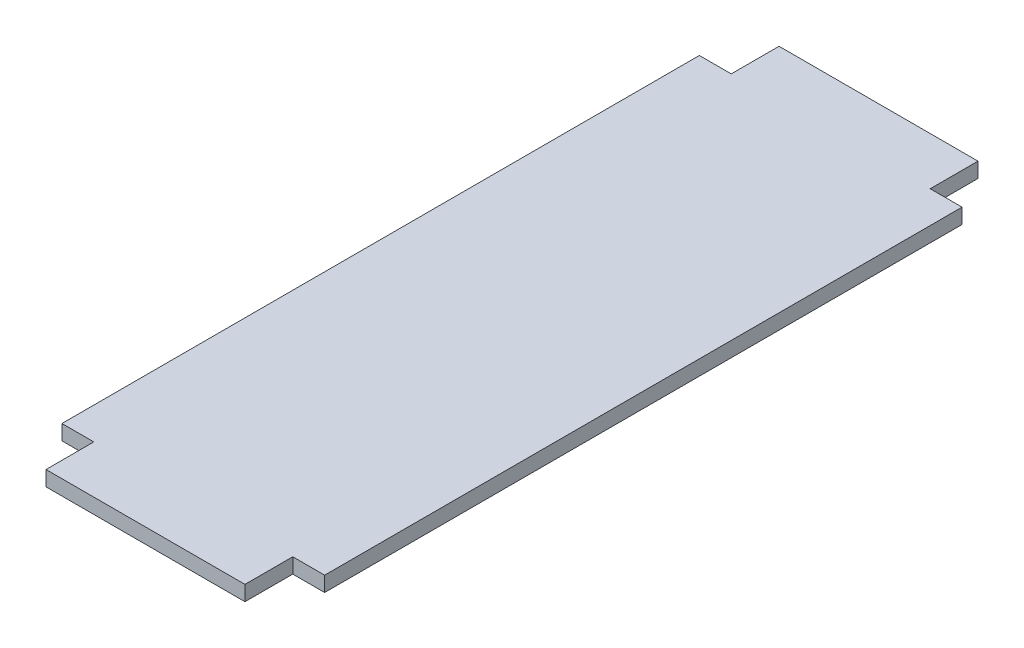
SolidWorks part; units mm, degrees
ref_plane "Front Plane" through (0, 0, 0) normal (0, 0, 1) x (1, 0, 0)
ref_plane "Top Plane" through (0, 0, 0) normal (0, 1, 0) x (1, 0, 0)
ref_plane "Right Plane" through (0, 0, 0) normal (1, 0, 0) x (0, 0, -1)
sketch "Sketch1" plane through (0, 0, 0) normal (0, 1, 0) x (1, 0, 0)
  line L0 (-26.169, 66.4972) -> (26.169, 66.4972) construction
  line L1 (26.169, -73.025) -> (-26.169, -73.025)
  line L2 (26.169, -73.025) -> (26.169, 73.025)
  line L3 (26.169, 73.025) -> (-26.169, 73.025)
  line L4 (-26.169, -73.025) -> (-26.169, 73.025)
  line L5 (26.169, -73.025) -> (-26.169, 73.025) construction
  line L6 (26.169, 73.025) -> (-26.169, -73.025) construction
  line L7 (-26.169, -66.4972) -> (26.169, -66.4972) construction
  line L8 (-26.169, 66.4972) -> (-26.169, -66.4972) construction
  line L9 (26.169, 66.4972) -> (26.169, -66.4972) construction
  line L35 (-26.169, 73.025) -> (-19.819, 73.025)
  line L36 (-26.169, 73.025) -> (-26.169, 63.5)
  line L37 (-26.169, 63.5) -> (-19.819, 63.5)
  line L38 (-19.819, 73.025) -> (-19.819, 63.5)
  line L39 (26.169, 73.025) -> (19.819, 73.025)
  line L40 (26.169, 73.025) -> (26.169, 63.5)
  line L41 (26.169, 63.5) -> (19.819, 63.5)
  line L42 (19.819, 73.025) -> (19.819, 63.5)
  line L43 (-26.169, -73.025) -> (-19.819, -73.025)
  line L44 (-26.169, -73.025) -> (-26.169, -63.5)
  line L45 (-26.169, -63.5) -> (-19.819, -63.5)
  line L46 (-19.819, -73.025) -> (-19.819, -63.5)
  line L47 (26.169, -73.025) -> (19.819, -73.025)
  line L48 (26.169, -73.025) -> (26.169, -63.5)
  line L49 (26.169, -63.5) -> (19.819, -63.5)
  line L50 (19.819, -73.025) -> (19.819, -63.5)
  point P0 (0, 0)
  point P10 (26.169, 0)
  point P11 (26.169, 0)
  dimension "D1" = 52.338
  dimension "D2" = 146.05
  dimension "D3" = 132.9944
  dimension "D4" = 127
  dimension "D5" = 6.35
extrude "Boss-Extrude1" add sketch "Sketch1" along normal blind 2.9972 contours L1 L50 L49 L2 L41 L42 L3 L38 L37 L4 L45 L46
